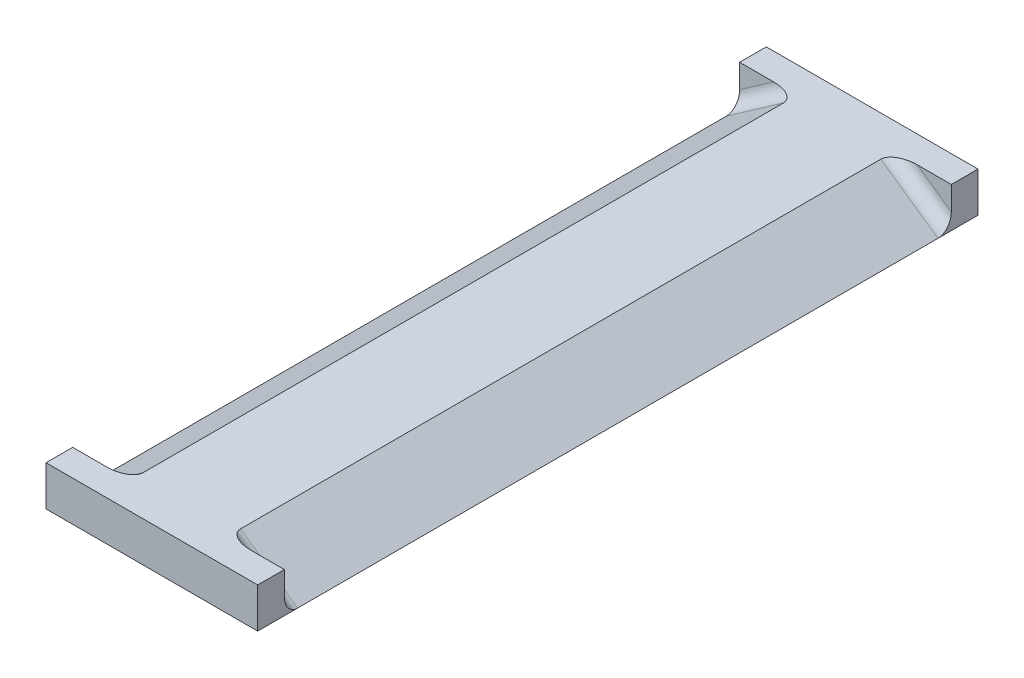
SolidWorks part; units mm, degrees
ref_plane "Front" through (0, 0, 0) normal (0, 0, 1) x (1, 0, 0)
ref_plane "Top" through (0, 0, 0) normal (0, 1, 0) x (1, 0, 0)
ref_plane "Right" through (0, 0, 0) normal (1, 0, 0) x (0, 0, -1)
sketch "Sketch1" plane through (0, 0, 0) normal (0, 0, 1) x (1, 0, 0)
  line L0 (0, 0) -> (-2.1422, -1.5)
  line L1 (-2.1422, -1.5) -> (5.7922, -1.5)
  line L2 (5.7922, -1.5) -> (3.65, 0)
  line L3 (3.65, 0) -> (0, 0)
  dimension "D1" = 3.65
  dimension "D2" = 35
  dimension "D3" = 35
  dimension "D4" = 1.5
extrude "Boss-Extrude1" add sketch "Sketch1" along normal blind 25
sketch "Sketch2" plane through (0, 0, 25) normal (0, 0, 1) x (1, 0, 0)
  line L0 (5.7922, -1.5) -> (3.65, 0) construction
  line L1 (-2.1422, -1.5) -> (5.7922, -1.5)
  line L2 (-2.1422, -1.5) -> (-2.1422, 0)
  line L3 (-2.1422, 0) -> (5.7922, 0)
  line L4 (5.7922, -1.5) -> (5.7922, 0)
  line L5 (-2.1422, -1.5) -> (5.7922, -1.5) construction
  line L6 (3.65, 0) -> (0, 0) construction
extrude "Boss-Extrude2" add sketch "Sketch2" along normal blind 1
sketch "Sketch3" plane through (0, 0, 0) normal (0, 0, -1) x (-1, 0, 0)
  line L1 (-5.7922, -1.5) -> (2.1422, -1.5)
  line L2 (-5.7922, -1.5) -> (-5.7922, 0)
  line L3 (-5.7922, 0) -> (2.1422, 0)
  line L4 (2.1422, -1.5) -> (2.1422, 0)
extrude "Boss-Extrude3" add sketch "Sketch3" along normal blind 1
fillet "Fillet1" radius 0.5 4 edges at (-1.0711, -0.75, 25) (4.7211, -0.75, 25) (4.7211, -0.75, 0) (-1.0711, -0.75, 0)
